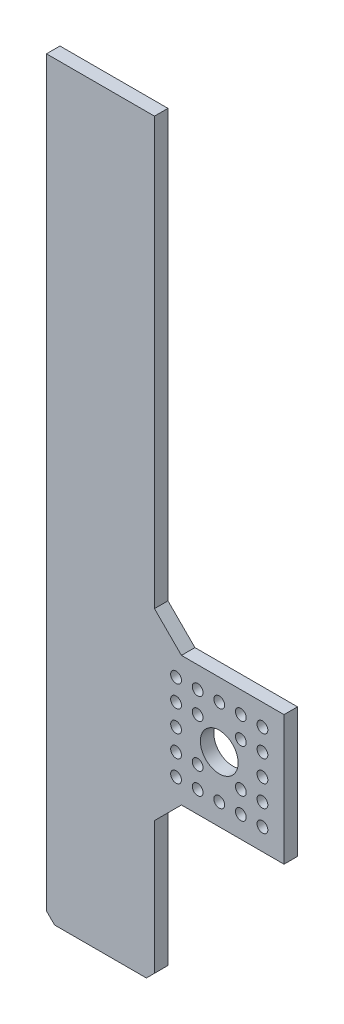
SolidWorks part; units mm, degrees
material "PMMA"
ref_plane "Front Plane" through (0, 0, 0) normal (0, 0, 1) x (1, 0, 0)
ref_plane "Top Plane" through (0, 0, 0) normal (0, 1, 0) x (1, 0, 0)
ref_plane "Right Plane" through (0, 0, 0) normal (1, 0, 0) x (0, 0, -1)
sketch "Sketch1" plane through (0, 0, 0) normal (0, 0, 1) x (1, 0, 0)
  line L0 (0, 0) -> (0, -278)
  line L1 (0, -278) -> (40, -278)
  line L2 (40, -278) -> (40, -216)
  line L3 (40, -216) -> (88, -216)
  line L4 (88, -216) -> (88, -168)
  line L5 (88, -168) -> (40, -168)
  line L6 (40, -168) -> (40, 0)
  line L7 (40, 0) -> (0, 0)
  line L8 (40, -168) -> (88, -216) construction
  line L9 (88, -168) -> (40, -216) construction
  line L10 (36.7207, -192) -> (92.7527, -192) construction
  line L11 (64, -162.6143) -> (64, -224.4365) construction
  circle A0 centre (64, -192) radius 7
  circle A1 centre (48, -176) radius 2
  circle A2 centre (56, -176) radius 2
  circle A3 centre (64, -176) radius 2
  circle A4 centre (72, -176) radius 2
  circle A5 centre (80, -176) radius 2
  circle A6 centre (56, -184) radius 2
  circle A8 centre (72, -184) radius 2
  circle A9 centre (80, -184) radius 2
  circle A13 centre (80, -192) radius 2
  circle A14 centre (56, -200) radius 2
  circle A16 centre (72, -200) radius 2
  circle A17 centre (80, -200) radius 2
  circle A18 centre (56, -208) radius 2
  circle A19 centre (64, -208) radius 2
  circle A20 centre (72, -208) radius 2
  circle A21 centre (80, -208) radius 2
  circle A22 centre (48, -184) radius 2
  circle A23 centre (48, -192) radius 2
  circle A24 centre (48, -200) radius 2
  circle A25 centre (48, -208) radius 2
  circle A26 centre (64, -184) radius 2 [skipped]
  circle A27 centre (56, -192) radius 2 [skipped]
  circle A28 centre (64, -192) radius 2 [skipped]
  circle A29 centre (72, -192) radius 2 [skipped]
  circle A30 centre (64, -200) radius 2 [skipped]
  dimension "D4" = 14
  dimension "D5" = 4
  dimension "D1" = 48
  dimension "D2" = 40
  dimension "D3" = 48
  dimension "D6" = 16
  dimension "D7" = 5
  dimension "D9" = 278
  dimension "D10" = 168
  dimension "D8" = 5
extrude "Boss-Extrude1" add sketch "Sketch1" along normal blind 5
chamfer "Chamfer2" distance 3 angle 45 2 edges at (0, -278, 2.5) (40, -278, 2.5)
chamfer "Chamfer3" distance 10 angle 45 2 edges at (40, -216, 2.5) (40, -168, 2.5)
